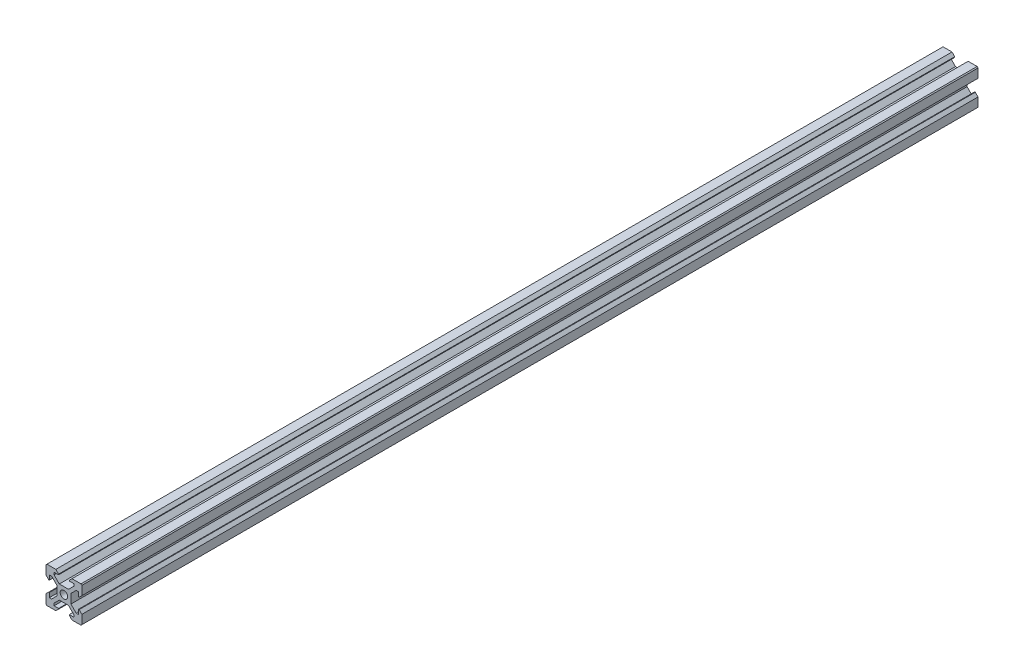
SolidWorks part; units mm, degrees
ref_plane "Front Plane" through (0, 0, 0) normal (0, 0, 1) x (1, 0, 0)
ref_plane "Top Plane" through (0, 0, 0) normal (0, 1, 0) x (1, 0, 0)
ref_plane "Right Plane" through (0, 0, 0) normal (1, 0, 0) x (0, 0, -1)
sketch "Sketch1" plane through (0, 0, 0) normal (0, 0, 1) x (1, 0, 0)
  line L0 (15.6876, 55.3211) -> (115.0437, 55.3211) construction
  line L1 (5.5, 6.8294) -> (2.5706, 3.9)
  line L2 (0, 3.9) -> (0, 2.1)
  line L3 (10, 10) -> (1.4849, 1.4849)
  line L4 (10, 10) -> (4.5, 10)
  line L5 (1.4849, 1.4849) -> (3.9, 3.9) construction
  line L6 (10, -10) -> (-10, 10) construction
  line L7 (10, 10) -> (1.4849, 1.4849) construction
  line L8 (0, 0) -> (-10, -10) construction
  line L10 (0, 3.9) -> (2.5706, 3.9)
  line L12 (-3.9, -3.9) -> (0, 0) construction
  line L13 (-3.9, 3.9) -> (3.9, -3.9) construction
  line L14 (5.5, 6.8294) -> (5.5, 8.12)
  line L15 (5.5, 8.12) -> (2.62, 8.12)
  line L16 (2.62, 8.12) -> (4.5, 10)
  line L17 (0, 2.1) -> (0, 16.7618) construction
  arc A0 (1.4849, 1.4849) -> (0, 2.1) centre (0, 0) ccw
  point P2 (0, 0)
  point P7 (0, 0)
  dimension "D3" = 45
  dimension "D4" = 6.1
  dimension "D8" = 4.2
  dimension "D1" = 20
  dimension "D2" = 11
  dimension "D5" = 1.88
  dimension "D6" = 9
  dimension "D7" = 0.94
  dimension "D9" = 3.9
extrude "Boss-Extrude1" add sketch "Sketch1" along normal blind 500
chamfer "Chamfer2" distance 0.5 angle 45 1 edges at (2.62, 8.12, 250)
mirror "Mirror1" about plane through (10, 10, 500) normal (-0.7071, 0.7071, 0) of bodies 102
chamfer "Chamfer1" distance 0.5 angle 45 1 edges at (10, 10, 250)
mirror "Mirror4" about plane through (0, 3.9, 500) normal (1, 0, 0) of bodies 103 104
mirror "Mirror5" about plane through (-3.9, 0, 500) normal (0, 1, 0) of bodies 105
